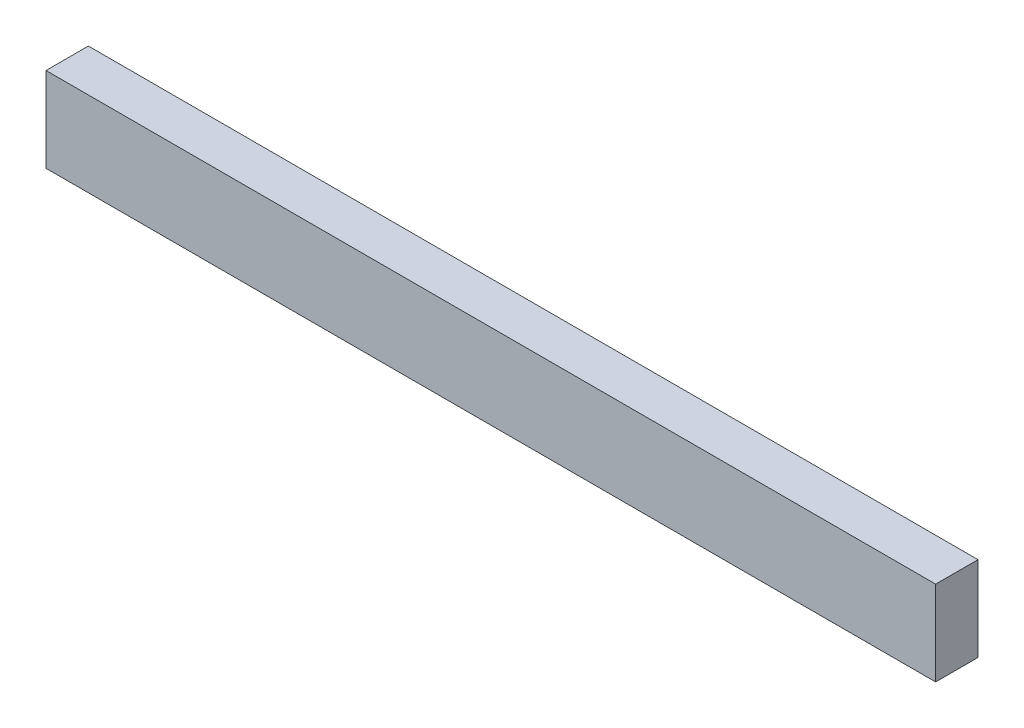
SolidWorks part; units mm, degrees
material "Balsa"
ref_plane "Alzado" through (0, 0, 0) normal (0, 0, 1) x (1, 0, 0)
ref_plane "Planta" through (0, 0, 0) normal (0, 1, 0) x (1, 0, 0)
ref_plane "Vista lateral" through (0, 0, 0) normal (1, 0, 0) x (0, 0, -1)
sketch "Croquis1" plane through (0, 0, 0) normal (1, 0, 0) x (0, 0, -1)
  line L1 (2.5, 5) -> (-2.5, 5)
  line L2 (2.5, 5) -> (2.5, -5)
  line L3 (2.5, -5) -> (-2.5, -5)
  line L4 (-2.5, 5) -> (-2.5, -5)
  line L5 (2.5, 5) -> (-2.5, -5) construction
  line L6 (2.5, -5) -> (-2.5, 5) construction
  point P0 (0, 0)
  dimension "D1" = 5
  dimension "D2" = 10
extrude "Saliente-Extruir1" add sketch "Croquis1" along normal blind 105
